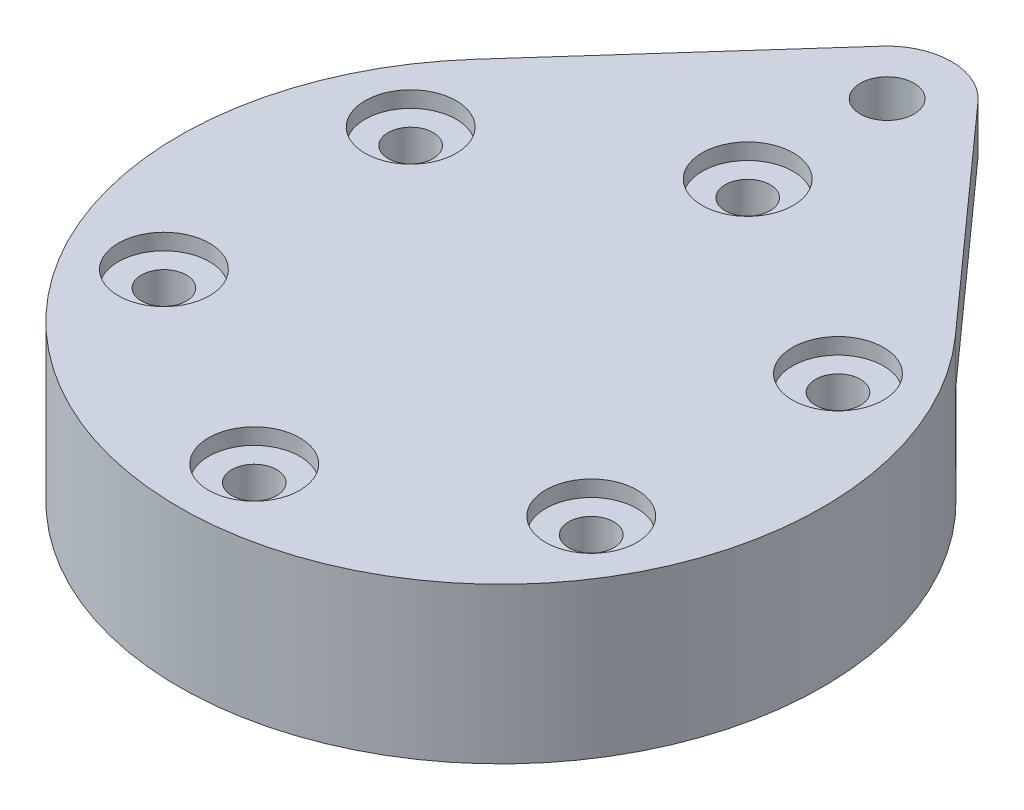
SolidWorks part; units mm, degrees
material "PEI"
ref_plane "Front Plane" through (0, 0, 0) normal (0, 0, 1) x (1, 0, 0)
ref_plane "Top Plane" through (0, 0, 0) normal (0, 1, 0) x (1, 0, 0)
ref_plane "Right Plane" through (0, 0, 0) normal (1, 0, 0) x (0, 0, -1)
sketch "Sketch1" plane through (0, 0, 0) normal (0, 1, 0) x (1, 0, 0)
  line L0 (-4.4721, 40) -> (-22.3607, 20)
  line L1 (4.4721, 40) -> (22.3607, 20)
  circle A0 centre (0, 0) radius 36 construction
  circle A1 centre (0, 36) radius 2.5
  circle A2 centre (0, 36) radius 6
  circle A3 centre (0, 0) radius 23 construction
  circle A4 centre (0, 0) radius 30
  point P26 (0, 0)
  dimension "D1" = 60
  dimension "D2" = 5
  dimension "D3" = 46
  dimension "D4" = 12
extrude "Boss-Extrude1" add sketch "Sketch1" along normal blind 4.5
sketch "Sketch2" plane through (0, 4.5, 0) normal (0, 1, 0) x (1, 0, 0)
  circle A0 centre (0, 0) radius 23 construction
  circle A1 centre (0, 23) radius 4.25
  circle A2 centre (19.9186, 11.5) radius 4.25
  circle A3 centre (19.9186, -11.5) radius 4.25
  circle A4 centre (0, -23) radius 4.25
  circle A5 centre (-19.9186, -11.5) radius 4.25
  circle A6 centre (-19.9186, 11.5) radius 4.25
  point P18 (0, 0)
  dimension "D1" = 8.5
  dimension "D2" = 6
extrude "Cut-Extrude1" cut sketch "Sketch2" against normal blind 1.5
sketch "Sketch3" plane through (0, 0, 0) normal (0, -1, 0) x (1, 0, 0)
  circle A0 centre (0, 0) radius 30
  dimension "D1" = 60
extrude "Boss-Extrude2" add sketch "Sketch3" along normal blind 10
sketch "Sketch4" plane through (0, 4.5, 0) normal (0, 1, 0) x (1, 0, 0)
  circle A0 centre (0, 0) radius 23 construction
  circle A1 centre (0, 23) radius 2.1
  circle A2 centre (19.9186, 11.5) radius 2.1
  circle A3 centre (19.9186, -11.5) radius 2.1
  circle A4 centre (0, -23) radius 2.1
  circle A5 centre (-19.9186, -11.5) radius 2.1
  circle A6 centre (-19.9186, 11.5) radius 2.1
  point P18 (0, 0)
  dimension "D1" = 4.2
extrude "Cut-Extrude2" cut sketch "Sketch4" against normal blind 43
